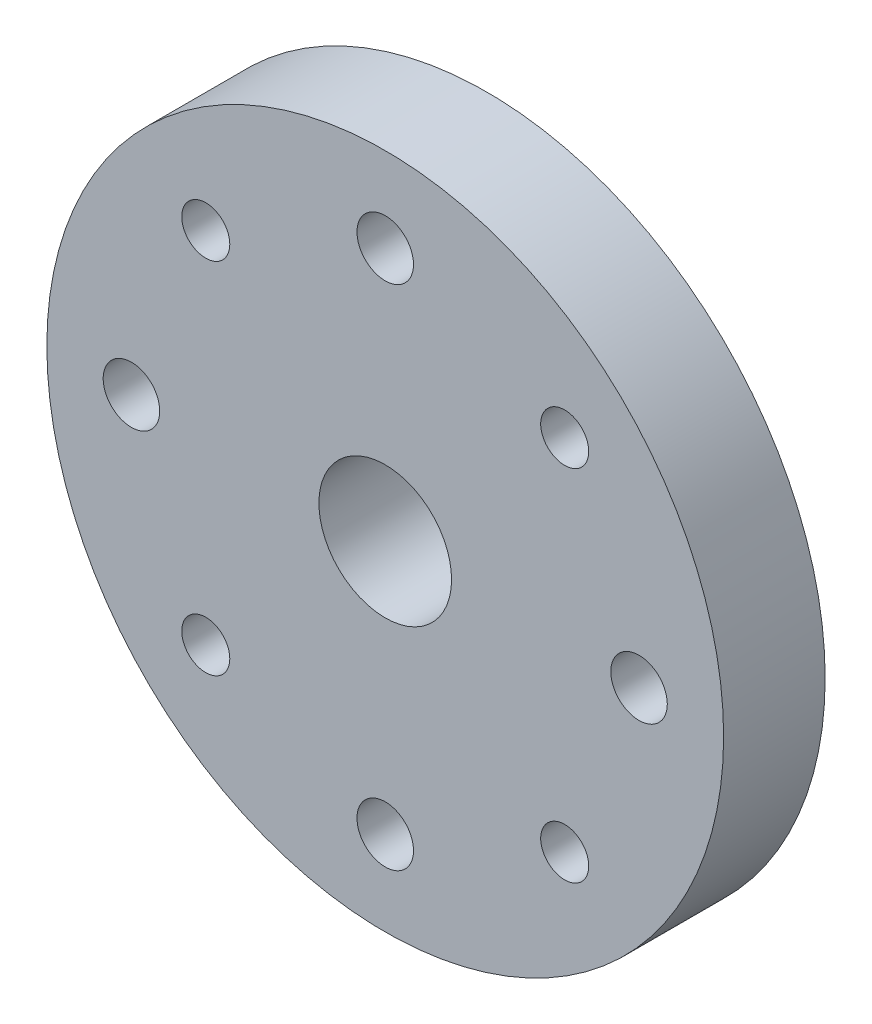
SolidWorks part; units mm, degrees
material "Balsa"
ref_plane "Front Plane" through (0, 0, 0) normal (0, 0, 1) x (1, 0, 0)
ref_plane "Top Plane" through (0, 0, 0) normal (0, 1, 0) x (1, 0, 0)
ref_plane "Right Plane" through (0, 0, 0) normal (1, 0, 0) x (0, 0, -1)
sketch "Sketch1" plane through (0, 0, 0) normal (0, 0, 1) x (1, 0, 0)
  circle A0 centre (0, 0) radius 20
  circle A1 centre (0, 0) radius 4
  circle A2 centre (0, 0) radius 15 construction
  circle A3 centre (0, 15) radius 1.75
  circle A4 centre (10.6066, 10.6066) radius 1.5
  circle A5 centre (15, 0) radius 1.75
  circle A6 centre (10.6066, -10.6066) radius 1.5
  circle A7 centre (0, -15) radius 1.75
  circle A8 centre (-10.6066, -10.6066) radius 1.5
  circle A9 centre (-15, 0) radius 1.75
  circle A10 centre (-10.6066, 10.6066) radius 1.5
  dimension "D1" = 40
  dimension "D2" = 8
  dimension "D3" = 30
  dimension "D4" = 3.5
  dimension "D5" = 3
  dimension "D6" = 45
  dimension "D7" = 4
extrude "Boss-Extrude1" add sketch "Sketch1" along normal blind 6
other "Move Face2" face at (4, 0, 6) face at (1.75, 15, 6) face at (12.1066, 10.6066, 6) face at (16.75, 0, 6) face at (12.1066, -10.6066, 6) face at (1.75, -15, 6) face at (-9.1066, -10.6066, 6) face at (-13.25, 0, 6) face at (-9.1066, 10.6066, 6) parameters "D1"=0.08
